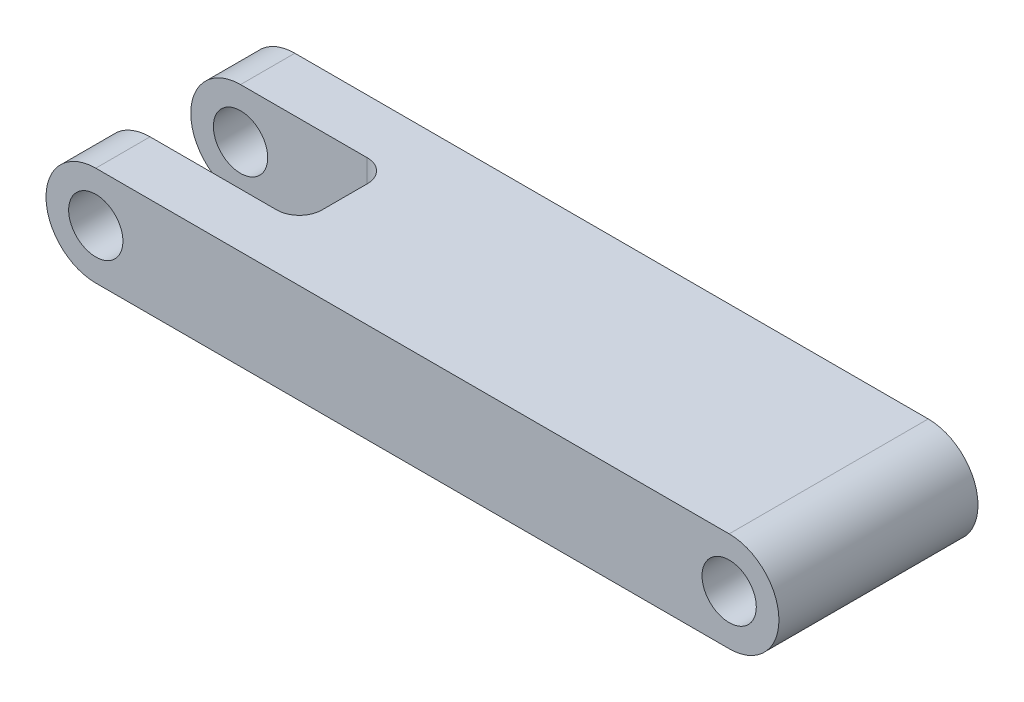
SolidWorks part; units mm, degrees
material "1023 Carbon Steel Sheet (SS)"
ref_plane "Plano frontal" through (0, 0, 0) normal (0, 0, 1) x (1, 0, 0)
ref_plane "Plano superior" through (0, 0, 0) normal (0, 1, 0) x (1, 0, 0)
ref_plane "Plano direito" through (0, 0, 0) normal (1, 0, 0) x (0, 0, -1)
sketch "Sketch1" plane through (0, 0, 0) normal (0, 0, 1) x (1, 0, 0)
  line L0 (0, 0) -> (140, 0) construction
  line L1 (0, 11) -> (140, 11)
  line L2 (0, -11) -> (140, -11)
  arc A0 (0, 11) -> (0, -11) centre (0, 0) ccw
  arc A1 (140, -11) -> (140, 11) centre (140, 0) ccw
  circle A2 centre (0, 0) radius 6
  circle A3 centre (140, 0) radius 6
  point P3 (70, 0)
  dimension "D1" = 12
  dimension "D2" = 22
  dimension "D3" = 140
extrude "Boss-Extrude1" add sketch "Sketch1" along normal blind 44
sketch "Sketch2" plane through (0, 11, 0) normal (0, 1, 0) x (1, 0, 0)
  line L0 (-11, 0) -> (-11, -44) construction
  line L1 (-55, -32) -> (33, -32)
  line L2 (-55, -32) -> (-55, -12)
  line L3 (-55, -12) -> (33, -12)
  line L4 (33, -32) -> (33, -12)
  line L5 (-55, -32) -> (33, -12) construction
  line L6 (-55, -12) -> (33, -32) construction
  line L7 (-11, -44) -> (0, -44) construction
  point P0 (-11, -22)
  dimension "D1" = 44
  dimension "D2" = 12
extrude "Cut-Extrude1" cut sketch "Sketch2" against normal through all
fillet "Fillet1" radius 5 2 edges at (33, 0, 32) (33, 0, 12)
ref_plane "Plane2" through (0, 0, 22) normal (0, 0, 1) x (1, 0, 0)
ref_plane "Plane3" through (0, 0, 13) normal (0, 0, 1) x (1, 0, 0)
